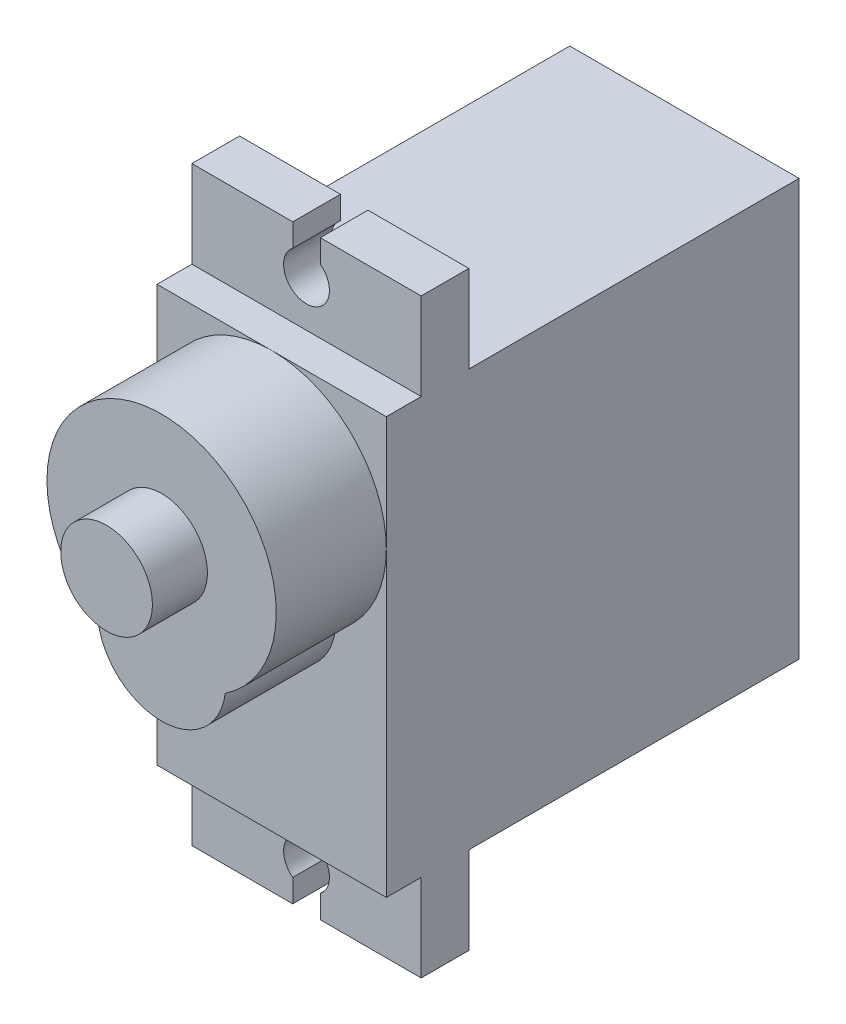
SolidWorks part; units mm, degrees
ref_plane "Front Plane" through (0, 0, 0) normal (1, 0, 0) x (0, 1, 0)
ref_plane "Top Plane" through (0, 0, 0) normal (0, 0, 1) x (0, 1, 0)
ref_plane "Right Plane" through (0, 0, 0) normal (0, 1, 0) x (-1, 0, 0)
sketch "Sketch2" plane through (0, 0, 0) normal (1, 0, 0) x (0, 1, 0)
  line L0 (0, 0) -> (0, 18)
  line L1 (0, 18) -> (-4.75, 18)
  line L2 (-4.75, 18) -> (-4.75, 20.6)
  line L3 (-4.75, 20.6) -> (0, 20.6)
  line L4 (0, 20.6) -> (0, 22.5)
  line L5 (0, 22.5) -> (22.7, 22.5)
  line L6 (22.7, 22.5) -> (22.7, 20.6)
  line L7 (22.7, 20.6) -> (27.45, 20.6)
  line L8 (27.45, 20.6) -> (27.45, 18)
  line L9 (27.45, 18) -> (22.7, 18)
  line L10 (22.7, 18) -> (22.7, 0)
  line L11 (22.7, 0) -> (0, 0)
  dimension "D1" = 18
  dimension "D2" = 22.5
  dimension "D3" = 2.6
  dimension "D4" = 32.2
  dimension "D5" = 2.6
  dimension "D6" = 22.7
extrude "Boss-Extrude1" add sketch "Sketch2" along normal blind 12.5
sketch "Sketch3" plane through (0, 0, 22.5) normal (0, 0, 1) x (1, 0, 0)
  line L0 (6.25, -23.4562) -> (6.25, 23.4562) construction
  line L2 (12.5, 0) -> (0, 0) construction
  line L3 (12.5, 22.7) -> (12.5, 0) construction
  line L4 (0, 22.7) -> (0, 0) construction
  line L5 (12.5, 22.7) -> (0, 22.7) construction
  circle A0 centre (6.25, 16.45) radius 6.25
  circle A1 centre (6.25, 11.7) radius 3.5
  point P4 (6.25, 8.2)
  point P7 (6.25, 0)
  point P13 (6.25, 22.7)
  dimension "D1" = 14.5
  dimension "D2" = 7
extrude "Boss-Extrude2" add sketch "Sketch3" along normal blind 6 contours A1 L0 A0 | L0 A1 A0 | A0 L0 A1 | L0 A0 A1 | A1 L0 A0 | L0 A1 A0
sketch "Sketch4" plane through (0, 0, 28.5) normal (0, 0, 1) x (1, 0, 0)
  circle A0 centre (6.25, 16.45) radius 2.5
  arc A1 (9.7213, 11.2526) -> (2.7787, 11.2526) centre (6.25, 16.45) ccw construction
  dimension "D1" = 5
extrude "Boss-Extrude3" add sketch "Sketch4" along normal blind 3
sketch "Sketch5" plane through (0, 0, 20.6) normal (0, 0, 1) x (1, 0, 0)
  line L0 (5.5, 27.45) -> (5.5, 26.2)
  line L1 (12.5, 27.45) -> (0, 27.45) construction
  line L2 (7, 26.2) -> (7, 27.45)
  line L3 (5.5, -3.5) -> (5.5, -4.75)
  line L4 (12.5, -4.75) -> (0, -4.75) construction
  line L5 (7, -3.5) -> (7, -4.75)
  line L6 (5.5, -4.75) -> (7, -4.75)
  line L7 (5.5, 27.45) -> (7, 27.45)
  line L8 (0, 27.45) -> (0, 22.7) construction
  circle A0 centre (6.25, 25.2) radius 1.25
  circle A1 centre (6.25, -2.5) radius 1.25
  point P9 (6.25, 27.45)
  line M7 (12.5, 27.45) -> (0, 27.45)
  dimension "D1" = 27.7
  dimension "D2" = 1.5
  dimension "D3" = 2.5
  dimension "D4" = 2.25
  dimension "D5" = 6.25
extrude "Cut-Extrude1" cut sketch "Sketch5" against normal up to surface (2.6 mm away) contours A0 L2 L0 M7 | A0 | A1 L3 L6 L5 | A1 up to face at (6.25, 25.075, 18)
